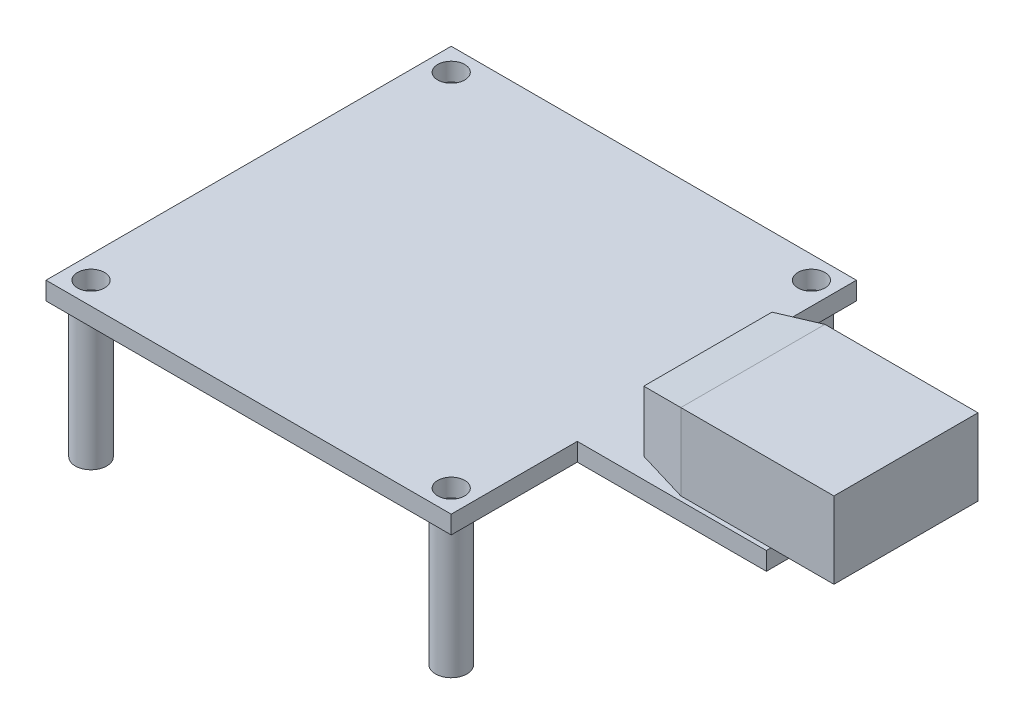
SolidWorks part; units mm, degrees
ref_plane "前视基准面" through (0, 0, 0) normal (0, 0, 1) x (1, 0, 0)
ref_plane "上视基准面" through (0, 0, 0) normal (0, 1, 0) x (1, 0, 0)
ref_plane "右视基准面" through (0, 0, 0) normal (1, 0, 0) x (0, 0, -1)
other "Configuration Table"
sketch "草图1" plane through (0, 0, 0) normal (0, 1, 0) x (1, 0, 0)
  line L0 (0, 0) -> (41.0231, 0) construction
  line L1 (-22.5, -22.5) -> (22.5, -22.5)
  line L2 (-22.5, -22.5) -> (-22.5, 22.5)
  line L3 (-22.5, 22.5) -> (22.5, 22.5)
  line L4 (22.5, -22.5) -> (22.5, 22.5)
  line L5 (-22.5, -22.5) -> (22.5, 22.5) construction
  line L6 (-22.5, 22.5) -> (22.5, -22.5) construction
  line L7 (0, 0) -> (0, 17.5958) construction
  line L9 (22.5, 8.5) -> (43.5, 8.5)
  line L10 (22.5, 8.5) -> (22.5, -8.5)
  line L11 (22.5, -8.5) -> (43.5, -8.5)
  line L12 (43.5, 8.5) -> (43.5, -8.5)
  circle A0 centre (-20, 20) radius 1.5
  circle A1 centre (20, 20) radius 1.5
  circle A2 centre (-20, -20) radius 1.5
  circle A3 centre (20, -20) radius 1.5
  point P0 (0, 0)
  point P21 (43.5, 0)
  dimension "D2" = 3
  dimension "D1" = 40
  dimension "D3" = 45
  dimension "D4" = 17
  dimension "D5" = 21
extrude "凸台-拉伸1" add sketch "草图1" along normal blind 2 contours L1 L4 L3 L2 A3 A1 A0 A2 | L12 L9 L4 L11
sketch "草图2" plane through (0, 0, 0) normal (0, -1, 0) x (1, 0, 0)
  line L0 (0, 0) -> (0, 5.5969) construction
  line L1 (0, 0) -> (6.6996, 0) construction
  circle A0 centre (-20, 20) radius 1.75
  circle A1 centre (-20, 20) radius 1
  circle A2 centre (20, 20) radius 1
  circle A3 centre (20, 20) radius 1.75
  circle A4 centre (20, -20) radius 1.75
  circle A5 centre (20, -20) radius 1
  circle A6 centre (-20, -20) radius 1
  circle A7 centre (-20, -20) radius 1.75
  dimension "D1" = 3.5
  dimension "D2" = 2
extrude "凸台-拉伸2" add sketch "草图2" along normal blind 15 separate body
sketch "草图5" plane through (43.5, 0, 0) normal (1, 0, 0) x (0, 0, -1)
  line L0 (8.5, 2) -> (-8.5, 2) construction
  line L1 (-8, 2) -> (8, 2)
  line L2 (-8, 2) -> (-8, 10.5)
  line L3 (-8, 10.5) -> (8, 10.5)
  line L4 (8, 2) -> (8, 10.5)
  point P6 (0, 10.5)
  dimension "D1" = 16
  dimension "D2" = 8.5
extrude "凸台-拉伸3" add sketch "草图5" against normal blind 10 and the other way blind 7 separate body
sketch "草图6" plane through (33.5, 0, 0) normal (-1, 0, 0) x (0, 0, 1)
  line L4 (8, 2) -> (8, 10.5)
  line L5 (8, 10.5) -> (-8, 10.5)
  line L6 (-8, 10.5) -> (-8, 2)
  line L7 (-8, 2) -> (8, 2)
  line L8 (8, 2) -> (8, 10.5)
  line L9 (8, 10.5) -> (-8, 10.5)
  line L10 (-8, 10.5) -> (-8, 2)
  line L11 (-8, 2) -> (8, 2)
  dimension "D1" = 0
extrude "凸台-拉伸4" add sketch "草图6" along normal blind 5 draft 10
